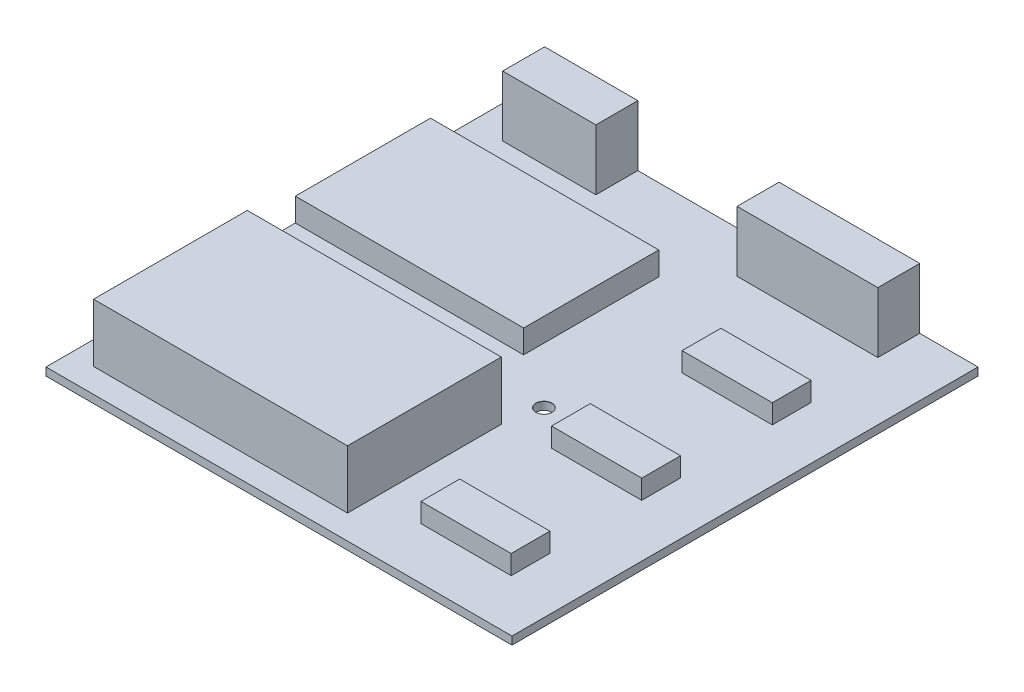
SolidWorks part; units mm, degrees
ref_plane "Front Plane" through (0, 0, 0) normal (0, 0, 1) x (1, 0, 0)
ref_plane "Top Plane" through (0, 0, 0) normal (0, 1, 0) x (1, 0, 0)
ref_plane "Right Plane" through (0, 0, 0) normal (1, 0, 0) x (0, 0, -1)
sketch "Sketch1" plane through (0, 0, 0) normal (0, 1, 0) x (1, 0, 0)
  line L1 (-50, -50) -> (50, -50)
  line L2 (-50, -50) -> (-50, 50)
  line L3 (-50, 50) -> (50, 50)
  line L4 (50, -50) -> (50, 50)
  line L5 (-50, -50) -> (50, 50) construction
  line L6 (-50, 50) -> (50, -50) construction
  point P0 (0, 0)
  dimension "D1" = 100
  dimension "D2" = 100
extrude "Boss-Extrude1" add sketch "Sketch1" along normal blind 1.7
sketch "Sketch2" plane through (0, 1.7, 0) normal (0, 1, 0) x (1, 0, 0)
  line L0 (50, 50) -> (-50, 50) construction
  line L1 (7.3, 50) -> (37.5, 50)
  line L2 (7.3, 50) -> (7.3, 41)
  line L3 (7.3, 41) -> (37.5, 41)
  line L4 (37.5, 50) -> (37.5, 41)
  line L5 (50, -50) -> (50, 50) construction
  line L6 (-50, 50) -> (-50, -50) construction
  line L7 (-43, 50) -> (-23, 50)
  line L8 (-43, 50) -> (-43, 41)
  line L9 (-43, 41) -> (-23, 41)
  line L10 (-23, 50) -> (-23, 41)
  dimension "D1" = 12.5
  dimension "D2" = 30.2
  dimension "D3" = 9
  dimension "D4" = 20
  dimension "D5" = 7
extrude "Boss-Extrude2" add sketch "Sketch2" along normal blind 13
sketch "Sketch3" plane through (0, 1.7, 0) normal (0, 1, 0) x (1, 0, 0)
  line L0 (-50, 50) -> (-50, -50) construction
  line L1 (-50, 32.5) -> (-1, 32.5)
  line L2 (-50, 32.5) -> (-50, 3.5)
  line L3 (-50, 3.5) -> (-1, 3.5)
  line L4 (-1, 32.5) -> (-1, 3.5)
  line L5 (7.3, 50) -> (-23, 50) construction
  dimension "D1" = 29
  dimension "D2" = 49
  dimension "D3" = 17.5
extrude "Boss-Extrude3" add sketch "Sketch3" along normal blind 5
sketch "Sketch4" plane through (0, 1.7, 0) normal (0, 1, 0) x (1, 0, 0)
  line L0 (-50, -50) -> (50, -50) construction
  line L1 (19.34, 25.48) -> (38.7, 25.48)
  line L2 (19.34, 25.48) -> (19.34, 17.16)
  line L3 (19.34, 17.16) -> (38.7, 17.16)
  line L4 (38.7, 25.48) -> (38.7, 17.16)
  line L5 (19.34, -10.86) -> (38.7, -10.86)
  line L6 (19.34, -10.86) -> (19.34, -2.54)
  line L7 (19.34, -2.54) -> (38.7, -2.54)
  line L8 (38.7, -10.86) -> (38.7, -2.54)
  line L9 (19.34, -30.56) -> (38.7, -30.56)
  line L10 (19.34, -30.56) -> (19.34, -38.88)
  line L11 (19.34, -38.88) -> (38.7, -38.88)
  line L12 (38.7, -30.56) -> (38.7, -38.88)
  line L13 (50, -50) -> (50, 50) construction
  point P12 (0, 0)
  dimension "D1" = 19.36
  dimension "D2" = 8.32
  dimension "D3" = 11.12
  dimension "D4" = 19.7
  dimension "D5" = 19.7
  dimension "D6" = 11.3
extrude "Boss-Extrude4" add sketch "Sketch4" along normal blind 4.13
sketch "Sketch5" plane through (0, 1.7, 0) normal (0, 1, 0) x (1, 0, 0)
  line L0 (-50, 3.5) -> (-50, -50) construction
  line L1 (-45, -11.8) -> (9.5, -11.8)
  line L2 (-45, -11.8) -> (-45, -44.8)
  line L3 (-45, -44.8) -> (9.5, -44.8)
  line L4 (9.5, -11.8) -> (9.5, -44.8)
  line L5 (-50, -50) -> (50, -50) construction
  dimension "D1" = 54.5
  dimension "D2" = 33
  dimension "D3" = 5
  dimension "D4" = 5.2
extrude "Boss-Extrude5" add sketch "Sketch5" along normal blind 12.5
sketch "Sketch6" plane through (0, 1.7, 0) normal (0, 1, 0) x (1, 0, 0)
  line L0 (-37, -4.15) -> (11, -4.15) construction
  line L1 (-50, 3.5) -> (-1, 3.5) construction
  line L2 (9.5, -11.8) -> (-45, -11.8) construction
  line L3 (-50, 3.5) -> (-50, -50) construction
  point P0 (-37, -4.15)
  point P1 (11, -4.15)
  point P4 (11.01, -4.5101)
  dimension "D1" = 48
  dimension "D2" = 13
hole_wizard "M3 Clearance Hole1" positions "Sketch7" profile "Sketch9" hole size "M3" standard "ANSI Metric" end condition through all
sketch "Sketch7" plane through (0, 1.7, 0) normal (0, 1, 0) x (1, 0, 0)
  point P0 (-37, -4.15)
  point P3 (11, -4.15)
sketch "Sketch9" plane through (-37, 1.7, 4.15) normal (1, 0, 0) x (0, 0, 1)
  line L0 (0, 0) -> (0, 1.7)
  line L1 (0, 1.7) -> (1.7, 1.7)
  line L2 (1.7, 1.7) -> (1.7, 0.025)
  line L3 (1.7, 0.025) -> (1.725, 0)
  line L5 (1.725, 0) -> (0, 0)
  line L6 (-1.7, 0.025) -> (-1.725, 0) construction
  line L11 (0, -6.35) -> (0, 107.95) construction
  dimension "Thru Hole Dia." = 3.4
  dimension "Thru Hole Depth" = 1.7
  dimension "Near C'Sink Dia." = 3.45
  dimension "Near C'Sink Angle" = 90
